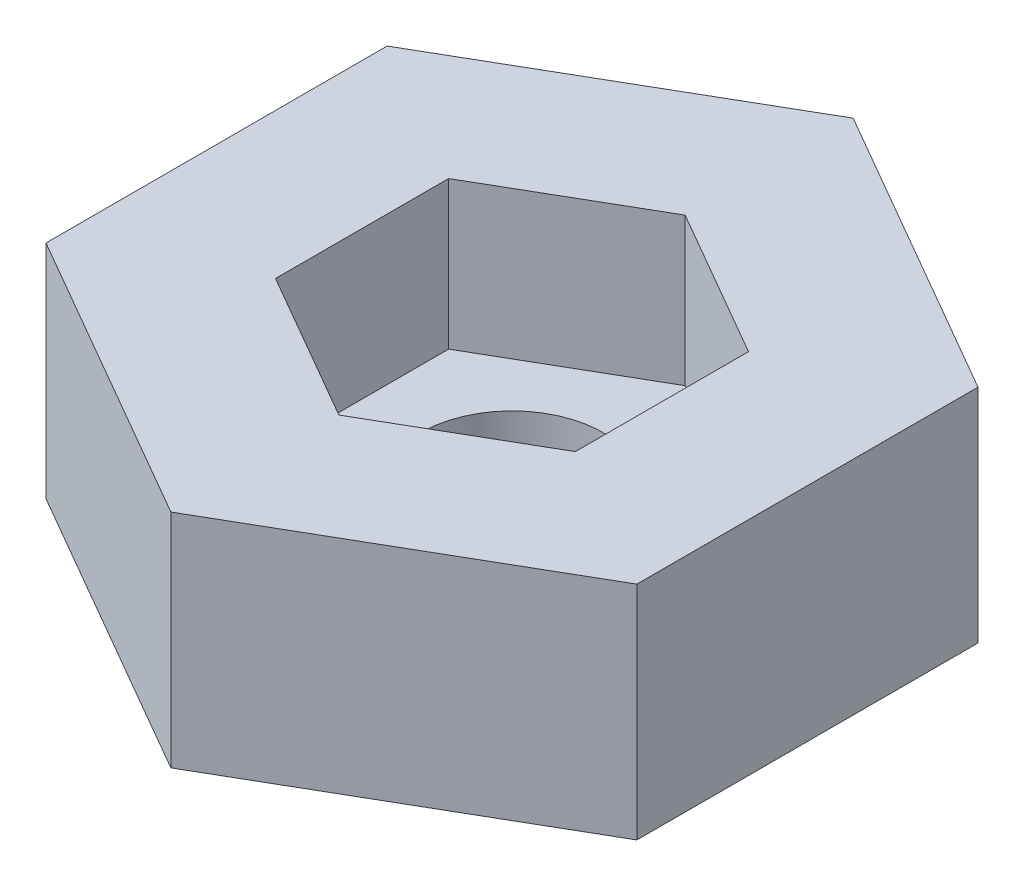
SolidWorks part; units mm, degrees
ref_plane "Front Plane" through (0, 0, 0) normal (0, 0, 1) x (1, 0, 0)
ref_plane "Top Plane" through (0, 0, 0) normal (0, 1, 0) x (1, 0, 0)
ref_plane "Right Plane" through (0, 0, 0) normal (1, 0, 0) x (0, 0, -1)
sketch "Sketch1" plane through (0, 0, 0) normal (0, 1, 0) x (1, 0, 0)
  line L1 (0, -11.547) -> (10, -5.7735)
  line L2 (10, -5.7735) -> (10, 5.7735)
  line L3 (10, 5.7735) -> (0, 11.547)
  line L4 (0, 11.547) -> (-10, 5.7735)
  line L5 (-10, 5.7735) -> (-10, -5.7735)
  line L6 (-10, -5.7735) -> (0, -11.547)
  circle A0 centre (0, 0) radius 10 construction
  circle A1 centre (0, 0) radius 3.1
  dimension "D2" = 6.2
  dimension "D1" = 20
extrude "Boss-Extrude1" add sketch "Sketch1" along normal mid plane 7.5
sketch "Sketch2" plane through (0, 3.75, 0) normal (0, 1, 0) x (1, 0, 0)
  line L1 (0, 5.8601) -> (-5.075, 2.9301)
  line L2 (-5.075, 2.9301) -> (-5.075, -2.9301)
  line L3 (-5.075, -2.9301) -> (0, -5.8601)
  line L4 (0, -5.8601) -> (5.075, -2.9301)
  line L5 (5.075, -2.9301) -> (5.075, 2.9301)
  line L6 (5.075, 2.9301) -> (0, 5.8601)
  circle A0 centre (0, 0) radius 5.075 construction
  dimension "D1" = 10.15
extrude "Cut-Extrude1" cut sketch "Sketch2" against normal blind 5
